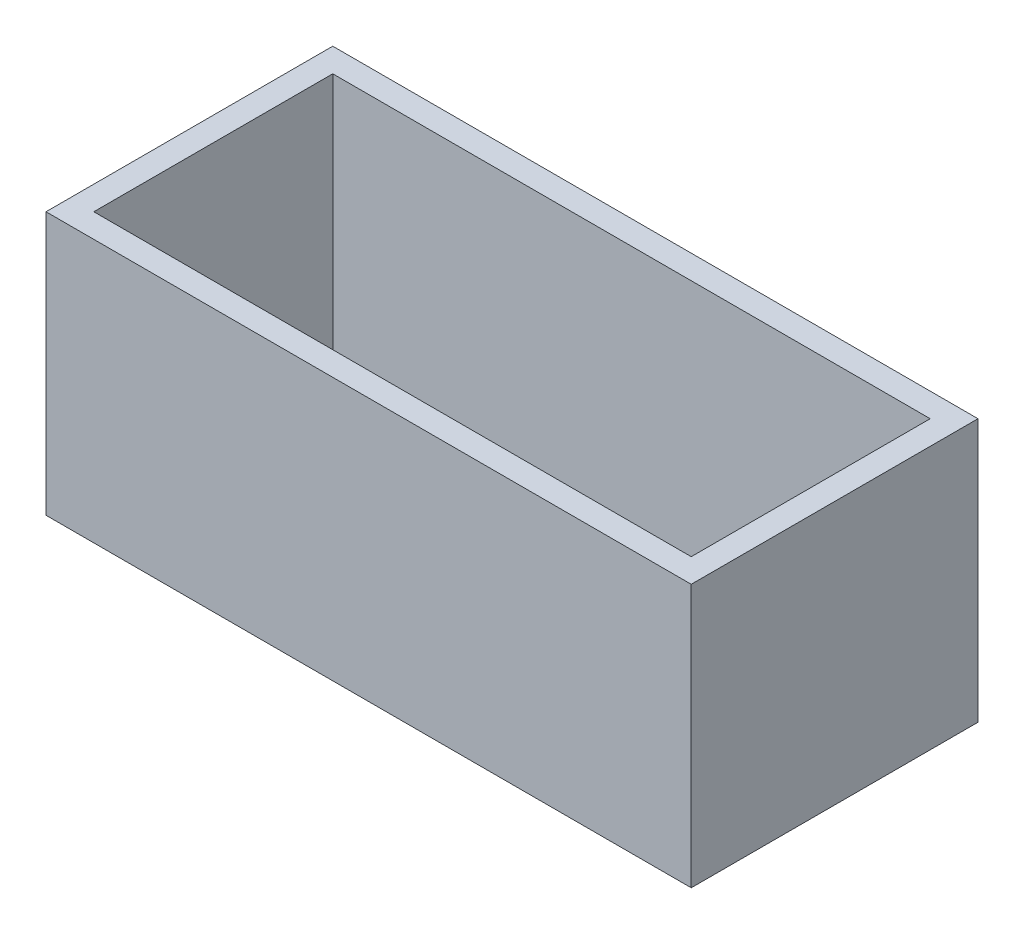
SolidWorks part; units mm, degrees
material "Silicon Dioxide"
ref_plane "Front Plane" through (0, 0, 0) normal (0, 0, 1) x (1, 0, 0)
ref_plane "Top Plane" through (0, 0, 0) normal (0, 1, 0) x (1, 0, 0)
ref_plane "Right Plane" through (0, 0, 0) normal (1, 0, 0) x (0, 0, -1)
sketch "Sketch8" plane through (0, 0, 0) normal (0, 1, 0) x (1, 0, 0)
  line L1 (-62.5, -25) -> (62.5, -25)
  line L2 (-62.5, -25) -> (-62.5, 25)
  line L3 (-62.5, 25) -> (62.5, 25)
  line L4 (62.5, -25) -> (62.5, 25)
  line L5 (-67.5, -30) -> (67.5, -30)
  line L6 (-67.5, -30) -> (-67.5, 30)
  line L7 (-67.5, 30) -> (67.5, 30)
  line L8 (67.5, -30) -> (67.5, 30)
  line L9 (-67.5, -30) -> (67.5, 30) construction
  line L10 (-67.5, 30) -> (67.5, -30) construction
  point P4 (0, -25)
  point P6 (-62.5, 0)
  point P7 (0, 0)
  dimension "D1" = 125
  dimension "D2" = 50
  dimension "D3" = 5
  dimension "D4" = 5
extrude "Boss-Extrude1" add sketch "Sketch8" along normal mid plane 50
sketch "Sketch9" plane through (-67.5, 0, 0) normal (-1, 0, 0) x (0, 0, 1)
  line L1 (-30, -25) -> (30, -25)
  line L2 (-30, -25) -> (-30, -30)
  line L3 (-30, -30) -> (30, -30)
  line L4 (30, -25) -> (30, -30)
  point P5 (0, 0)
  dimension "D1" = 5
extrude "Boss-Extrude2" add sketch "Sketch9" against normal up to surface (135 mm away) up to face at (67.5, 0, 0)
